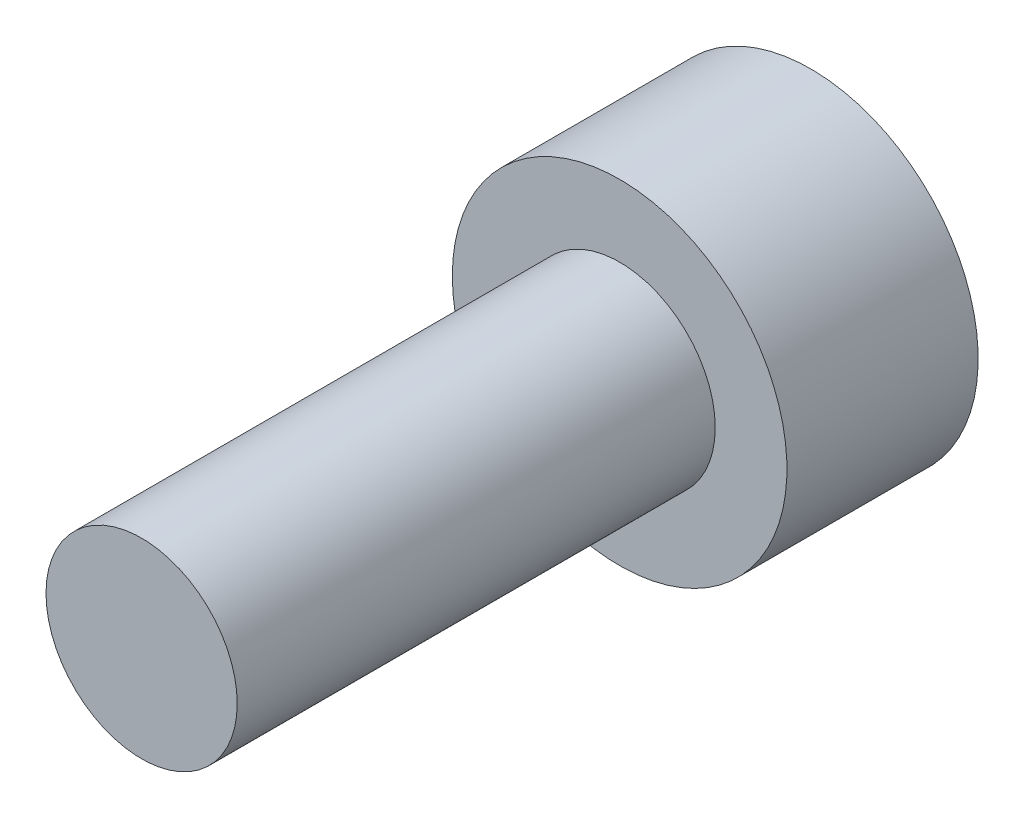
SolidWorks part; units mm, degrees
ref_plane "前视基准面" through (0, 0, 0) normal (0, 0, 1) x (1, 0, 0)
ref_plane "上视基准面" through (0, 0, 0) normal (0, 1, 0) x (1, 0, 0)
ref_plane "右视基准面" through (0, 0, 0) normal (1, 0, 0) x (0, 0, -1)
sketch "草图1" plane through (0, 0, 0) normal (0, 1, 0) x (1, 0, 0)
  line L0 (0, 0) -> (2, 0)
  line L1 (2, 0) -> (2, 10)
  line L2 (2, 10) -> (3.5, 10)
  line L3 (3.5, 10) -> (3.5, 14)
  line L4 (3.5, 14) -> (0, 14)
  line L5 (0, 14) -> (0, 0) construction
  line L6 (0, 0) -> (0, 14)
  dimension "D1" = 4
  dimension "D2" = 4
  dimension "D3" = 10
  dimension "D4" = 3.5
revolve "旋转1" add sketch "草图1" angle 360 about L5
sketch "草图2" plane through (0, 0, -14) normal (0, 0, -1) x (-1, 0, 0)
  line L1 (0, 2.1939) -> (-1.9, 1.097)
  line L2 (-1.9, 1.097) -> (-1.9, -1.097)
  line L3 (-1.9, -1.097) -> (0, -2.1939)
  line L4 (0, -2.1939) -> (1.9, -1.097)
  line L5 (1.9, -1.097) -> (1.9, 1.097)
  line L6 (1.9, 1.097) -> (0, 2.1939)
  circle A0 centre (0, 0) radius 1.1991 construction
  circle A1 centre (0, 0) radius 1.9 construction
  dimension "D1" = 3.8
extrude "切除-拉伸1" cut sketch "草图2" against normal blind 2
